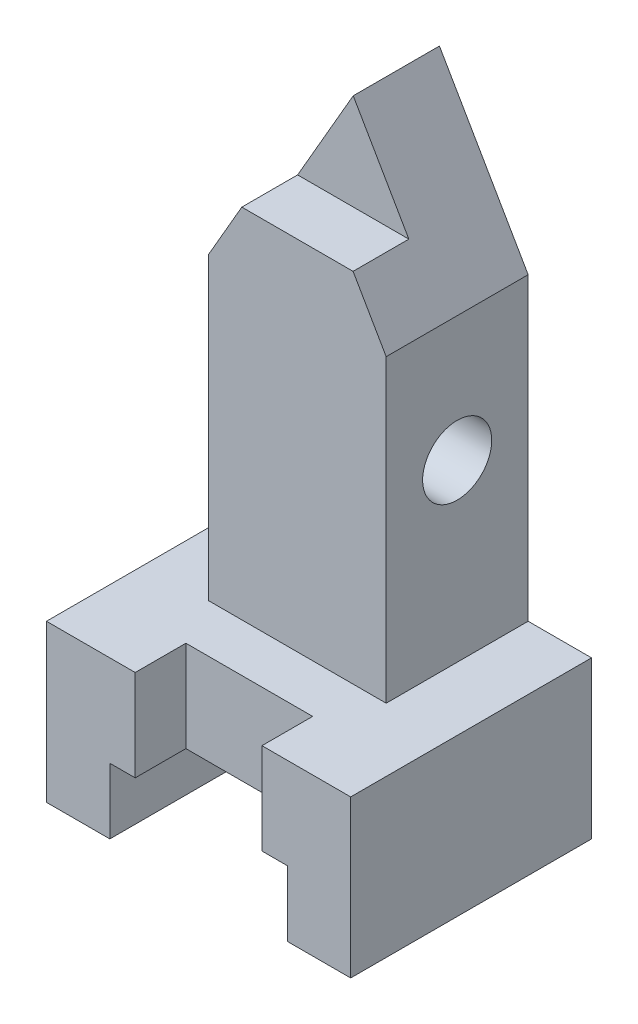
SolidWorks part; units mm, degrees
material "1023 Carbon Steel Sheet (SS)"
ref_plane "Front Plane" through (0, 0, 0) normal (0, 0, 1) x (1, 0, 0)
ref_plane "Top Plane" through (0, 0, 0) normal (0, 1, 0) x (1, 0, 0)
ref_plane "Right Plane" through (0, 0, 0) normal (1, 0, 0) x (0, 0, -1)
sketch "Sketch1" plane through (0, 0, 0) normal (0, 0, 1) x (1, 0, 0)
  line L0 (0, 143.2) -> (0, -44.8) construction
  line L1 (-17.6669, 112.6) -> (-28, 94.7026)
  line L2 (0, 143.2) -> (-17.6669, 112.6)
  line L4 (17.6669, 112.6) -> (0, 143.2)
  line L5 (17.6669, 112.6) -> (28, 94.7026)
  line L6 (-28, 94.7026) -> (-28, 0)
  line L7 (28, 94.7026) -> (28, 0)
  line L8 (0, 0) -> (-28, 0)
  line L9 (28, 0) -> (0, 0)
  line L11 (0, 112.6) -> (17.6669, 112.6) [skipped]
  circle A0 centre (0, 122.8) radius 10.2 construction
  dimension "D1" = 44.8
  dimension "D2" = 188
  dimension "D4" = 60
  dimension "D5" = 28
extrude "Boss-Extrude1" add sketch "Sketch1" along normal mid plane 44.8
sketch "Sketch2" plane through (28, 0, 0) normal (1, 0, 0) x (0, 0, -1)
  line L0 (-22.4, 0) -> (22.4, 0) construction
  line L1 (22.4, 0) -> (22.4, 94.7026) construction
  circle A0 centre (0, 55.2) radius 10.9082
  dimension "D1" = 55.2
  dimension "D2" = 22.4
extrude "Cut-Extrude1" cut sketch "Sketch2" against normal through all
sketch "Sketch3" plane through (0, 0, 22.4) normal (0, 0, 1) x (1, 0, 0)
  line L1 (-37.1883, 152.1589) -> (33.7867, 152.1589)
  line L2 (-37.1883, 152.1589) -> (-37.1883, 112.8)
  line L3 (-37.1883, 112.8) -> (33.7867, 112.8)
  line L4 (33.7867, 152.1589) -> (33.7867, 112.8)
  dimension "D1" = 30.4
extrude "Cut-Extrude2" cut sketch "Sketch3" against normal blind 17.6
sketch "Sketch4" plane through (0, 0, 0) normal (0, 0, 1) x (1, 0, 0)
  line L0 (-28, 0) -> (28, 0) construction
  line L1 (-28, 0) -> (28, 0)
  line L2 (-48, 0) -> (0, 0)
  line L3 (0, 0) -> (48, 0)
  line L4 (-48, 0) -> (-48, -49.4899)
  line L5 (-48, -49.4899) -> (-28, -49.4899)
  line L6 (-28, -49.4899) -> (-28, -28.8)
  line L7 (-28, -28.8) -> (28, -28.8)
  line L8 (28, -28.8) -> (28, -49.4899)
  line L9 (28, -49.4899) -> (48, -49.4899)
  line L10 (48, -49.4899) -> (48, 0)
  dimension "D1" = 48
  dimension "D2" = 48
  dimension "D3" = 56
  dimension "D4" = 28.8
extrude "Boss-Extrude3" add sketch "Sketch4" along normal blind 53.6 and the other way blind 22.4 contours L9 L10 L3 L1 L2 L4 L5 L6 L7 L8
sketch "Sketch7" plane through (0, 0, 53.6) normal (0, 0, 1) x (1, 0, 0)
  line L0 (0, 0) -> (0, -28.8) construction
  line L1 (-28, -28.8) -> (28, -28.8) construction
  line L3 (-20, 32.5118) -> (20, 32.5118)
  line L4 (-20, 32.5118) -> (-20, -61.3118)
  line L5 (-20, -61.3118) -> (20, -61.3118)
  line L6 (20, 32.5118) -> (20, -61.3118)
  line L7 (-20, 32.5118) -> (20, -61.3118) construction
  line L8 (-20, -61.3118) -> (20, 32.5118) construction
  point P5 (0, -14.4)
  dimension "D1" = 40
extrude "Cut-Extrude4" cut sketch "Sketch7" against normal blind 16
sketch "Sketch8" plane through (0, 0, 0) normal (1, 0, 0) x (0, 0, -1)
  line L0 (-22.4, 0) -> (-51.556, 0) construction
  line L1 (22.4, 0) -> (-53.6, 0) construction
  line L2 (-22.4, 0) -> (-53.6, 0)
  point P4 (0, 0)
  dimension "D1" = 31.2
